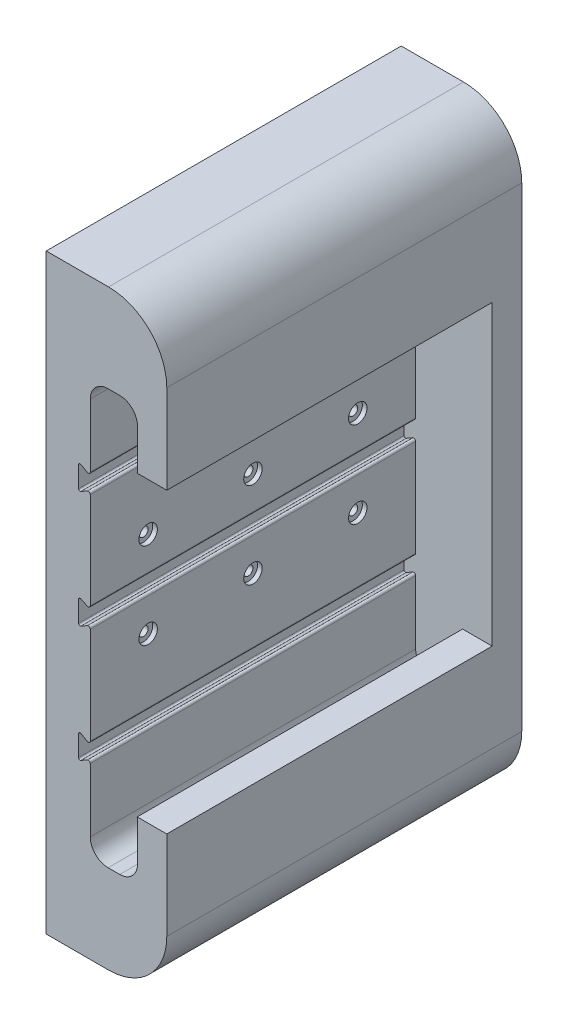
SolidWorks part; units mm, degrees
ref_plane "Front Plane" through (0, 0, 0) normal (1, 0, 0) x (0, 1, 0)
ref_plane "Top Plane" through (0, 0, 0) normal (0, 0, 1) x (0, 1, 0)
ref_plane "Right Plane" through (0, 0, 0) normal (0, 1, 0) x (-1, 0, 0)
sketch "Sketch1" plane through (0, 0, 0) normal (0, 0, 1) x (0, 1, 0)
  line L0 (-43.0362, 0) -> (-84.3709, 0)
  line L1 (-177.8, -25) -> (-177.8, -25.4)
  line L2 (-170.3, -20) -> (-152.8, -20)
  line L3 (-152.8, -20) -> (-152.8, -32.7)
  line L4 (-152.8, -32.7) -> (-190.9, -32.7)
  line L5 (-215.9, -7.7) -> (-215.9, 19.05)
  line L6 (-215.9, 19.05) -> (38.1, 19.05)
  line L7 (38.1, 19.05) -> (38.1, -7.7)
  line L8 (13.1, -32.7) -> (-25, -32.7)
  line L9 (-25, -32.7) -> (-25, -20)
  line L10 (-25, -20) -> (-7.5, -20)
  line L11 (0, -20) -> (0, -19.6)
  line L14 (-93.4061, 5) -> (-84.3939, 5)
  line L15 (-83.9407, 4.2887) -> (-85.2772, 1.4226)
  line L17 (-88.9, 19.05) -> (-88.9, 5)
  line L18 (-170.3, 0) -> (-143.0362, 0)
  line L20 (-92.2514, 1.5) -> (-93.8391, 4.25)
  line L21 (-177.8, -12.5) -> (-177.8, -7.5)
  line L24 (0, -7.5) -> (0, -12.5)
  line L25 (-113.9, 0) -> (-113.9, 19.05) construction
  line L26 (-63.9, 0) -> (-63.9, 19.05) construction
  line L27 (-143.7579, 4.25) -> (-142.1702, 1.5)
  line L28 (-134.3939, 5) -> (-143.3249, 5)
  line L29 (-135.5486, 1.5) -> (-133.9609, 4.25)
  line L30 (-35.5486, 1.5) -> (-33.9609, 4.25)
  line L31 (-34.3939, 5) -> (-43.3249, 5)
  line L32 (-43.7579, 4.25) -> (-42.1702, 1.5)
  line L33 (-134.6826, 0) -> (-93.1174, 0)
  line L34 (-34.6826, 0) -> (-7.5, 0)
  line L35 (-143.8878, 4.175) -> (-142.3001, 1.425)
  line L36 (-134.3939, 5.15) -> (-143.3249, 5.15)
  line L37 (-135.4187, 1.425) -> (-133.831, 4.175)
  line L38 (-134.6826, 0.15) -> (-93.1174, 0.15)
  line L39 (-92.3813, 1.425) -> (-93.969, 4.175)
  line L40 (-93.4061, 5.15) -> (-84.3939, 5.15)
  line L41 (-83.8048, 4.2253) -> (-85.1413, 1.3592)
  line L42 (-43.0362, 0.15) -> (-84.3709, 0.15)
  line L43 (-43.8878, 4.175) -> (-42.3001, 1.425)
  line L44 (-34.3939, 5.15) -> (-43.3249, 5.15)
  line L45 (-35.4187, 1.425) -> (-33.831, 4.175)
  line L46 (-34.6826, 0.15) -> (-7.5, 0.15)
  line L47 (0.15, -7.5) -> (0.15, -12.5)
  line L48 (-24.85, -20.15) -> (-7.5, -20.15)
  line L49 (-24.85, -32.55) -> (-24.85, -20.15)
  line L50 (13.1, -32.55) -> (-24.85, -32.55)
  line L51 (37.95, 18.9) -> (37.95, -7.7)
  line L52 (-215.75, 18.9) -> (37.95, 18.9)
  line L53 (-215.75, -7.7) -> (-215.75, 18.9)
  line L54 (-152.95, -32.55) -> (-190.9, -32.55)
  line L55 (-152.95, -20.15) -> (-152.95, -32.55)
  line L56 (-170.3, -20.15) -> (-152.95, -20.15)
  line L57 (-177.95, -12.5) -> (-177.95, -7.5)
  line L58 (-170.3, 0.15) -> (-143.0362, 0.15)
  line L59 (-152.95, -20.15) -> (-152.95, -20)
  line L60 (-24.85, -20.15) -> (-24.85, -20)
  arc A0 (38.1, -7.7) -> (13.1, -32.7) centre (13.1, -7.7) cw
  arc A1 (-190.9, -32.7) -> (-215.9, -7.7) centre (-190.9, -7.7) cw
  arc A2 (0, -7.5) -> (-7.5, 0) centre (-7.5, -7.5) ccw
  arc A3 (-7.5, -20) -> (0, -12.5) centre (-7.5, -12.5) ccw
  arc A4 (-170.3, -20) -> (-177.8, -12.5) centre (-170.3, -12.5) cw
  arc A5 (-177.8, -7.5) -> (-170.3, 0) centre (-170.3, -7.5) cw
  arc A6 (-143.0362, 0) -> (-142.1702, 1.5) centre (-143.0362, 1) ccw
  arc A7 (-93.1174, 0) -> (-92.2514, 1.5) centre (-93.1174, 1) ccw
  arc A8 (-135.5486, 1.5) -> (-134.6826, 0) centre (-134.6826, 1) ccw
  arc A9 (-85.2772, 1.4226) -> (-84.3709, 0) centre (-84.3709, 1) ccw
  arc A10 (-43.0362, 0) -> (-42.1702, 1.5) centre (-43.0362, 1) ccw
  arc A11 (-35.5486, 1.5) -> (-34.6826, 0) centre (-34.6826, 1) ccw
  arc A12 (-33.9609, 4.25) -> (-34.3939, 5) centre (-34.3939, 4.5) ccw
  arc A13 (-43.3249, 5) -> (-43.7579, 4.25) centre (-43.3249, 4.5) ccw
  arc A14 (-84.3939, 5) -> (-83.9407, 4.2887) centre (-84.3939, 4.5) cw
  arc A15 (-93.8391, 4.25) -> (-93.4061, 5) centre (-93.4061, 4.5) cw
  arc A16 (-134.3939, 5) -> (-133.9609, 4.25) centre (-134.3939, 4.5) cw
  arc A17 (-143.7579, 4.25) -> (-143.3249, 5) centre (-143.3249, 4.5) cw
  arc A18 (-143.0362, 0.15) -> (-142.3001, 1.425) centre (-143.0362, 1) ccw
  arc A19 (-143.8878, 4.175) -> (-143.3249, 5.15) centre (-143.3249, 4.5) cw
  arc A20 (-134.3939, 5.15) -> (-133.831, 4.175) centre (-134.3939, 4.5) cw
  arc A21 (-135.4187, 1.425) -> (-134.6826, 0.15) centre (-134.6826, 1) ccw
  arc A22 (-93.1174, 0.15) -> (-92.3813, 1.425) centre (-93.1174, 1) ccw
  arc A23 (-93.969, 4.175) -> (-93.4061, 5.15) centre (-93.4061, 4.5) cw
  arc A24 (-84.3939, 5.15) -> (-83.8048, 4.2253) centre (-84.3939, 4.5) cw
  arc A25 (-85.1413, 1.3592) -> (-84.3709, 0.15) centre (-84.3709, 1) ccw
  arc A26 (-43.0362, 0.15) -> (-42.3001, 1.425) centre (-43.0362, 1) ccw
  arc A27 (-43.3249, 5.15) -> (-43.8878, 4.175) centre (-43.3249, 4.5) ccw
  arc A28 (-33.831, 4.175) -> (-34.3939, 5.15) centre (-34.3939, 4.5) ccw
  arc A29 (-35.4187, 1.425) -> (-34.6826, 0.15) centre (-34.6826, 1) ccw
  arc A30 (0.15, -7.5) -> (-7.5, 0.15) centre (-7.5, -7.5) ccw
  arc A31 (-7.5, -20.15) -> (0.15, -12.5) centre (-7.5, -12.5) ccw
  arc A32 (37.95, -7.7) -> (13.1, -32.55) centre (13.1, -7.7) cw
  arc A33 (-190.9, -32.55) -> (-215.75, -7.7) centre (-190.9, -7.7) cw
  arc A34 (-170.3, -20.15) -> (-177.95, -12.5) centre (-170.3, -12.5) cw
  arc A35 (-177.95, -7.5) -> (-170.3, 0.15) centre (-170.3, -7.5) cw
  point P20 (0, 0)
  point P23 (-177.8, 0)
  point P24 (-88.9, 19.05)
  point P25 (0, 0)
  point P59 (-85.9406, 0)
  point P71 (-33.5279, 5)
  point P74 (-44.1909, 5)
  point P77 (-83.6091, 5)
  point P80 (-94.2721, 5)
  point P83 (-133.5279, 5)
  point P86 (-144.1909, 5)
  dimension "D8" = 25
  dimension "D9" = 7.5
  dimension "D7" = 25
  dimension "D11" = 1
  dimension "D16" = 1
  dimension "D17" = 1
  dimension "D18" = 1
  dimension "D19" = 1
  dimension "D25" = 0.5
  dimension "D1" = 177.8
  dimension "D2" = 60
  dimension "D3" = 25
  dimension "D4" = 19.05
  dimension "D5" = 254
  dimension "D6" = 12.7
  dimension "D10" = 65
  dimension "D12" = 5
  dimension "D13" = 20
  dimension "D14" = 177.8
  dimension "D15" = 25
  dimension "D20" = 10.6631
  dimension "D21" = 60
  dimension "D22" = 60
  dimension "D23" = 60
  dimension "D24" = 60
  dimension "D26" = 0.15
extrude "Boss-Extrude1" add sketch "Sketch1" along normal blind 152.4
sketch "Sketch2" plane through (0, 0, 0) normal (0, 0, -1) x (1, 0, 0)
  line L0 (-19.05, 215.9) -> (-19.05, -38.1)
  line L2 (32.7, 25) -> (32.7, 152.8)
  line L3 (32.7, 152.8) -> (32.7, 190.9)
  line L5 (-19.05, -38.1) -> (7.7, -38.1)
  line L6 (7.7, -38.1) -> (32.7, 25)
  line L7 (-19.05, 215.9) -> (7.7, 215.9)
  line L8 (7.7, 215.9) -> (32.7, 190.9)
extrude "Boss-Extrude2" add sketch "Sketch2" against normal blind 12.7
sketch "Sketch3" plane through (-0.15, 0, 0) normal (1, 0, 0) x (0, 1, 0)
  line L0 (-134.6826, 82.55) -> (-43.0362, 82.55) construction
  line L1 (-107.2442, 127.55) -> (-107.2442, 37.55)
  line L3 (-134.6826, 127.55) -> (-42.8058, 127.55) construction
  line L4 (-134.6826, 37.55) -> (-42.8058, 37.55) construction
  line L5 (-88.7442, 127.55) -> (-88.7442, 37.55) construction
  line L6 (-84.3709, 152.4) -> (-84.3709, 12.7) construction
  line L7 (-84.3709, 12.7) -> (-43.0362, 12.7) construction
  line L8 (-43.0362, 12.7) -> (-43.0362, 152.4) construction
  line L9 (-43.0362, 152.4) -> (-84.3709, 152.4) construction
  line L10 (-134.6826, 12.7) -> (-93.1174, 12.7) construction
  line L11 (-93.1174, 12.7) -> (-93.1174, 152.4) construction
  line L12 (-93.1174, 152.4) -> (-134.6826, 152.4) construction
  line L13 (-134.6826, 152.4) -> (-134.6826, 12.7) construction
  line L14 (-84.3709, 152.4) -> (-84.3709, 12.7)
  line L15 (-84.3709, 12.7) -> (-43.0362, 12.7)
  line L16 (-43.0362, 12.7) -> (-43.0362, 152.4)
  line L17 (-43.0362, 152.4) -> (-84.3709, 152.4)
  line L18 (-134.6826, 12.7) -> (-93.1174, 12.7)
  line L19 (-93.1174, 12.7) -> (-93.1174, 152.4)
  line L20 (-93.1174, 152.4) -> (-134.6826, 152.4)
  line L21 (-134.6826, 152.4) -> (-134.6826, 12.7)
  line L22 (-93.1174, 152.4) -> (-84.3709, 152.4)
  line L23 (-88.7442, 152.4) -> (-88.7442, 12.7)
  line L24 (-88.7442, 12.7) -> (-84.3709, 12.7)
  circle A0 centre (-107.2442, 82.55) radius 1.9844
  circle A1 centre (-107.2442, 127.55) radius 1.9844
  circle A2 centre (-107.2442, 37.55) radius 1.9844
  circle A3 centre (-70.2442, 37.55) radius 1.9844
  circle A4 centre (-70.2442, 82.55) radius 1.9844
  circle A5 centre (-70.2442, 127.55) radius 1.9844
  point P30 (-107.2442, 82.55)
  point P31 (-88.7442, 82.55)
  point P32 (-107.2442, 82.55)
  point P33 (-113.8459, 82.55)
  point P34 (0, 0)
  point P35 (-43.0362, 82.55)
  dimension "D2" = 3.9688
  dimension "D4" = 45
  dimension "D5" = 45
  dimension "D6" = 18.5
extrude "Cut-Extrude1" cut sketch "Sketch3" against normal blind 25
sketch "Sketch4" plane through (-0.15, 0, 0) normal (1, 0, 0) x (0, 1, 0)
  circle A26 centre (-107.2442, 127.55) radius 3.9687
  circle A27 centre (-107.2442, 82.55) radius 3.9687
  circle A28 centre (-107.2442, 37.55) radius 3.9687
  circle A29 centre (-70.2442, 37.55) radius 3.9687
  circle A30 centre (-70.2442, 82.55) radius 3.9687
  circle A31 centre (-70.2442, 127.55) radius 3.9687
  dimension "D1" = 7.9375
extrude "Cut-Extrude2" cut sketch "Sketch4" against normal blind 2
